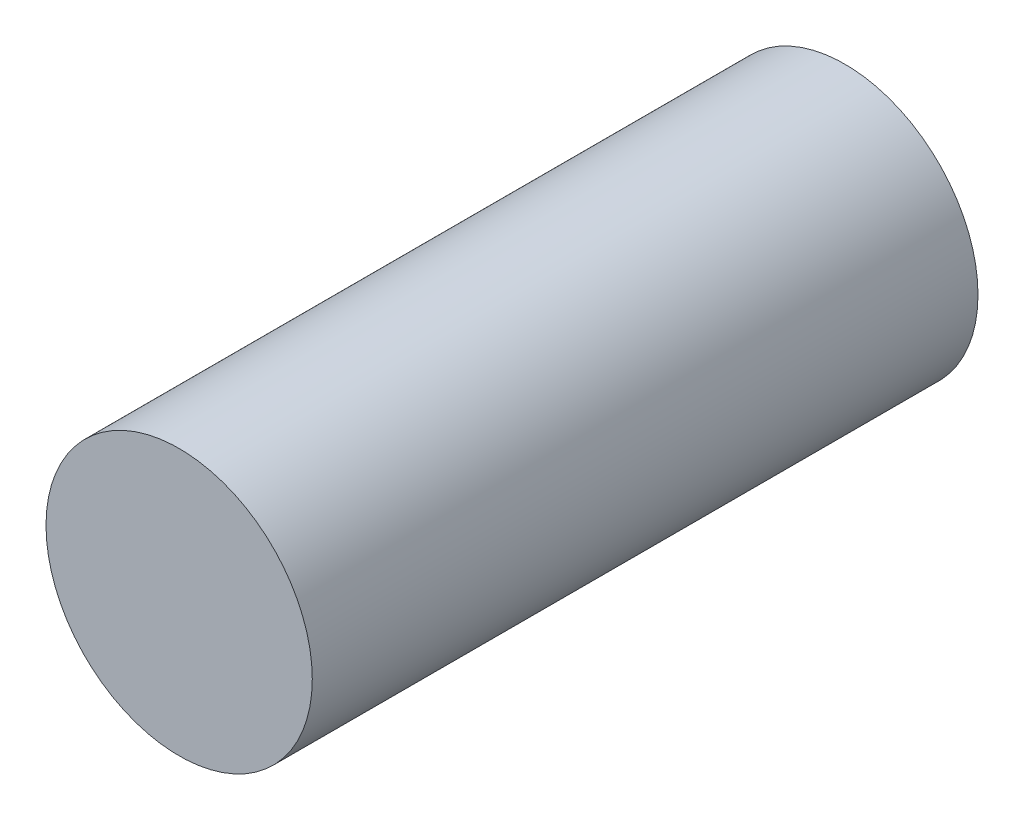
SolidWorks part; units mm, degrees
ref_plane "Front Plane" through (0, 0, 0) normal (0, 0, 1) x (1, 0, 0)
ref_plane "Top Plane" through (0, 0, 0) normal (0, 1, 0) x (1, 0, 0)
ref_plane "Right Plane" through (0, 0, 0) normal (1, 0, 0) x (0, 0, -1)
sketch "Sketch1" plane through (0, 0, 0) normal (0, 0, 1) x (1, 0, 0)
  circle A0 centre (0, 0) radius 1
extrude "Boss-Extrude1" add sketch "Sketch1" along normal blind 5
